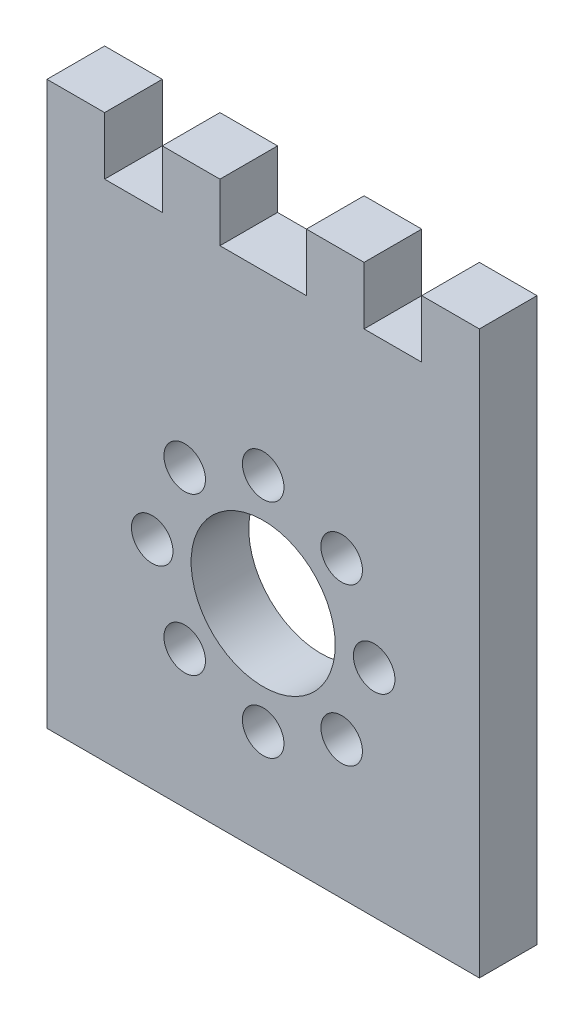
SolidWorks part; units mm, degrees
ref_plane "Front Plane" through (0, 0, 0) normal (0, 0, 1) x (1, 0, 0)
ref_plane "Top Plane" through (0, 0, 0) normal (0, 1, 0) x (1, 0, 0)
ref_plane "Right Plane" through (0, 0, 0) normal (1, 0, 0) x (0, 0, -1)
sketch "Sketch1" plane through (0, 0, 0) normal (0, 0, 1) x (1, 0, 0)
  line L1 (-16.5554, 15.7616) -> (21.5446, 15.7616)
  line L2 (-16.5554, 15.7616) -> (-16.5554, -35.0384)
  line L3 (-16.5554, -35.0384) -> (21.5446, -35.0384)
  line L4 (21.5446, 15.7616) -> (21.5446, -35.0384)
  dimension "D1" = 50.8
  dimension "D2" = 38.1
extrude "Boss-Extrude1" add sketch "Sketch1" along normal blind 5.08
sketch "Sketch2" plane through (0, 0, 5.08) normal (0, 0, 1) x (1, 0, 0)
  line L0 (2.4946, 15.7616) -> (2.4946, -35.0384) construction
  line L1 (21.5446, 15.7616) -> (-16.5554, 15.7616) construction
  line L2 (-16.5554, -35.0384) -> (21.5446, -35.0384) construction
  line L3 (-16.5554, -9.6384) -> (21.5446, -9.6384) construction
  line L4 (-16.5554, 15.7616) -> (-16.5554, -35.0384) construction
  line L5 (21.5446, -35.0384) -> (21.5446, 15.7616) construction
  circle A0 centre (2.4946, -9.6384) radius 6.35
  circle A1 centre (12.2736, -9.6384) radius 1.8288
  circle A2 centre (9.4094, -16.5532) radius 1.8288
  circle A3 centre (2.4946, -19.4174) radius 1.8288
  circle A4 centre (-4.4202, -16.5532) radius 1.8288
  circle A5 centre (-7.2844, -9.6384) radius 1.8288
  circle A6 centre (-4.4202, -2.7236) radius 1.8288
  circle A7 centre (2.4946, 0.1406) radius 1.8288
  circle A8 centre (9.4094, -2.7236) radius 1.8288
  point P12 (2.4946, -9.6384)
  point P33 (2.4946, -9.6384)
  dimension "D1" = 12.7
  dimension "D2" = 3.6576
  dimension "D3" = 9.779
  dimension "D4" = 8
extrude "Cut-Extrude1" cut sketch "Sketch2" against normal blind 5.08
sketch "Sketch3" plane through (0, 0, 5.08) normal (0, 0, 1) x (1, 0, 0)
  line L0 (2.4946, 15.7616) -> (2.4946, -35.0384) construction
  line L1 (21.5446, 15.7616) -> (-16.5554, 15.7616) construction
  line L2 (-16.5554, -35.0384) -> (21.5446, -35.0384) construction
  line L3 (21.5446, -9.6384) -> (-16.5554, -9.6384) construction
  line L4 (21.5446, -35.0384) -> (21.5446, 15.7616) construction
  line L5 (-16.5554, 15.7616) -> (-16.5554, -35.0384) construction
  line L6 (-16.5554, 15.7616) -> (-16.5554, 20.8416)
  line L7 (6.3046, 15.7616) -> (11.3846, 15.7616)
  line L8 (6.3046, 15.7616) -> (6.3046, 20.8416)
  line L9 (6.3046, 20.8416) -> (11.3846, 20.8416)
  line L10 (11.3846, 15.7616) -> (11.3846, 20.8416)
  line L11 (16.4646, 15.7616) -> (21.5446, 15.7616)
  line L12 (16.4646, 15.7616) -> (16.4646, 20.8416)
  line L13 (16.4646, 20.8416) -> (21.5446, 20.8416)
  line L14 (21.5446, 15.7616) -> (21.5446, 20.8416)
  line L15 (-11.4754, 20.8416) -> (-16.5554, 20.8416)
  line L16 (-11.4754, 15.7616) -> (-11.4754, 20.8416)
  line L17 (-11.4754, 15.7616) -> (-16.5554, 15.7616)
  line L18 (-6.3954, 15.7616) -> (-6.3954, 20.8416)
  line L19 (-1.3154, 20.8416) -> (-6.3954, 20.8416)
  line L20 (-1.3154, 15.7616) -> (-1.3154, 20.8416)
  line L21 (-1.3154, 15.7616) -> (-6.3954, 15.7616)
  line L22 (-1.3154, -35.0384) -> (-6.3954, -35.0384)
  line L23 (-1.3154, -35.0384) -> (-1.3154, -40.1184)
  line L24 (-1.3154, -40.1184) -> (-6.3954, -40.1184)
  line L25 (-6.3954, -35.0384) -> (-6.3954, -40.1184)
  line L26 (-11.4754, -35.0384) -> (-16.5554, -35.0384)
  line L27 (-11.4754, -35.0384) -> (-11.4754, -40.1184)
  line L28 (-11.4754, -40.1184) -> (-16.5554, -40.1184)
  line L29 (21.5446, -35.0384) -> (21.5446, -40.1184)
  line L30 (16.4646, -40.1184) -> (21.5446, -40.1184)
  line L31 (16.4646, -35.0384) -> (16.4646, -40.1184)
  line L32 (16.4646, -35.0384) -> (21.5446, -35.0384)
  line L33 (11.3846, -35.0384) -> (11.3846, -40.1184)
  line L34 (6.3046, -40.1184) -> (11.3846, -40.1184)
  line L35 (6.3046, -35.0384) -> (6.3046, -40.1184)
  line L36 (6.3046, -35.0384) -> (11.3846, -35.0384)
  line L37 (-16.5554, -35.0384) -> (-16.5554, -40.1184)
  dimension "D1" = 3.81
  dimension "D2" = 5.08
  dimension "D3" = 5.08
  dimension "D4" = 5.08
  dimension "D5" = 5.08
  dimension "D6" = 5.08
extrude "Boss-Extrude2" add sketch "Sketch3" against normal blind 5.08
sketch "Sketch4" plane through (0, -40.1184, 0) normal (0, -1, 0) x (1, 0, 0)
  line L1 (-16.5554, 5.08) -> (21.5446, 5.08)
  line L2 (-16.5554, 5.08) -> (-16.5554, 0)
  line L3 (-16.5554, 0) -> (21.5446, 0)
  line L4 (21.5446, 5.08) -> (21.5446, 0)
extrude "Cut-Extrude2" cut sketch "Sketch4" against normal blind 11.43
